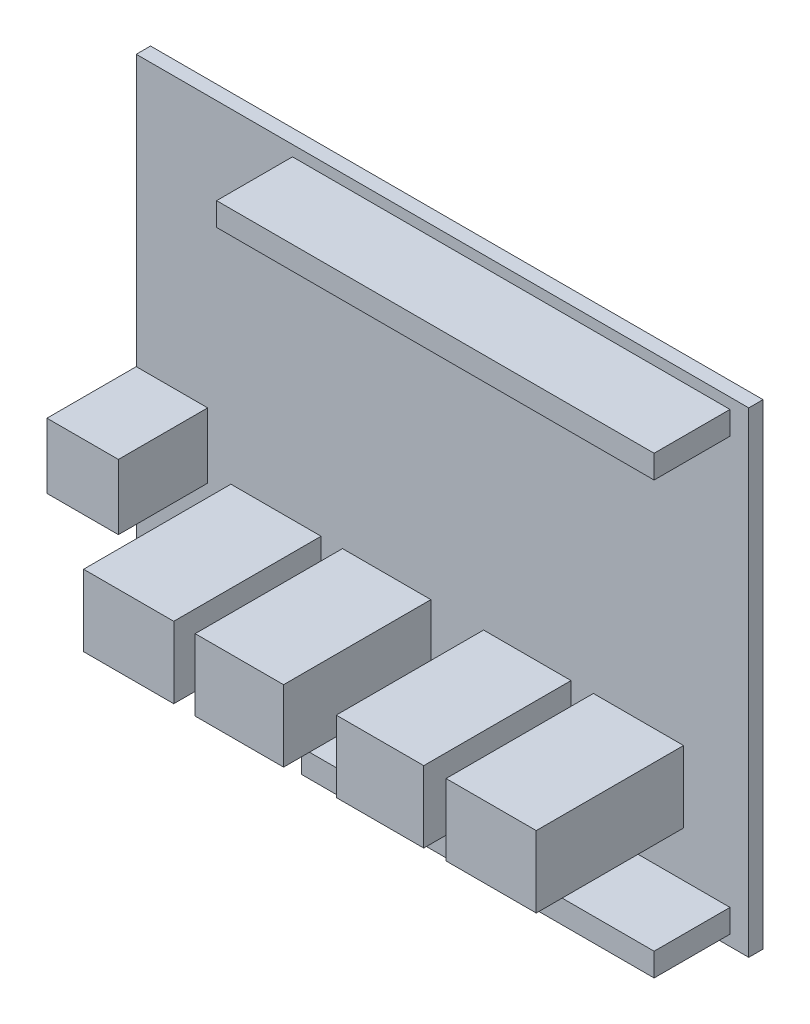
SolidWorks part; units mm, degrees
ref_plane "Front Plane" through (0, 0, 0) normal (0, 0, 1) x (1, 0, 0)
ref_plane "Top Plane" through (0, 0, 0) normal (0, 1, 0) x (1, 0, 0)
ref_plane "Right Plane" through (0, 0, 0) normal (1, 0, 0) x (0, 0, -1)
sketch "Sketch1" plane through (0, 0, 0) normal (0, 0, 1) x (1, 0, 0)
  line L0 (0, 0) -> (68.6, 0)
  line L1 (68.6, 0) -> (68.6, 53.3)
  line L2 (68.6, 53.3) -> (0, 53.3)
  line L3 (0, 53.3) -> (0, 0)
extrude "Boss-Extrude1" add sketch "Sketch1" along normal blind 1.6
sketch "Sketch2" plane through (0, 0, 0) normal (0, 0, 1) x (1, 0, 0)
  line L0 (10.6, 8.9) -> (20.7, 8.9)
  line L1 (20.7, 8.9) -> (20.7, 16.9)
  line L2 (20.7, 16.9) -> (10.6, 16.9)
  line L3 (10.6, 16.9) -> (10.6, 8.9)
  line L4 (23.1, 8.9) -> (33, 8.9)
  line L5 (33, 8.9) -> (33, 16.9)
  line L6 (33, 16.9) -> (23.1, 16.9)
  line L7 (23.1, 16.9) -> (23.1, 8.9)
  line L8 (38.9, 8.9) -> (48.7, 8.9)
  line L9 (48.7, 8.9) -> (48.7, 16.9)
  line L10 (48.7, 16.9) -> (38.9, 16.9)
  line L11 (38.9, 16.9) -> (38.9, 8.9)
  line L12 (51.2, 8.9) -> (61.3, 8.9)
  line L13 (61.3, 8.9) -> (61.3, 16.9)
  line L14 (61.3, 16.9) -> (51.2, 16.9)
  line L15 (51.2, 16.9) -> (51.2, 8.9)
extrude "Boss-Extrude2" add sketch "Sketch2" along normal blind 18.1
sketch "Sketch3" plane through (0, 0, 0) normal (0, 0, 1) x (1, 0, 0)
  line L0 (0, 15.7) -> (8, 15.7)
  line L1 (8, 15.7) -> (8, 23)
  line L2 (8, 23) -> (0, 23)
  line L3 (0, 23) -> (0, 15.7)
extrude "Boss-Extrude3" add sketch "Sketch3" along normal blind 11.6
sketch "Sketch4" plane through (0, 0, 0) normal (0, 0, 1) x (1, 0, 0)
  line L0 (17.5, 49.5) -> (66.5, 49.5)
  line L1 (66.5, 49.5) -> (66.5, 52.1)
  line L2 (66.5, 52.1) -> (17.5, 52.1)
  line L3 (17.5, 52.1) -> (17.5, 49.5)
  line L4 (27, 1.2) -> (66.5, 1.2)
  line L5 (66.5, 1.2) -> (66.5, 3.8)
  line L6 (66.5, 3.8) -> (27, 3.8)
  line L7 (27, 3.8) -> (27, 1.2)
extrude "Boss-Extrude4" add sketch "Sketch4" along normal blind 10.1
